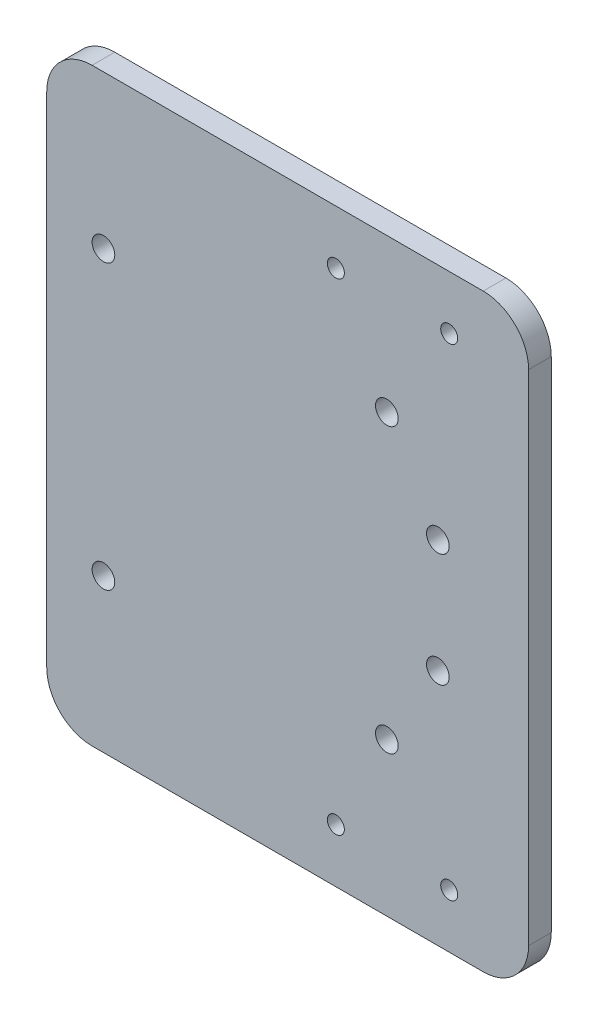
SolidWorks part; units mm, degrees
ref_plane "前视基准面" through (0, 0, 0) normal (0, 0, 1) x (1, 0, 0)
ref_plane "上视基准面" through (0, 0, 0) normal (0, 1, 0) x (1, 0, 0)
ref_plane "右视基准面" through (0, 0, 0) normal (1, 0, 0) x (0, 0, -1)
sketch "草图1" plane through (0, 0, 0) normal (0, 0, 1) x (1, 0, 0)
  line L1 (-56.1003, 41.4797) -> (28.8997, 41.4797)
  line L2 (-56.1003, 41.4797) -> (-56.1003, -62.5203)
  line L3 (-56.1003, -62.5203) -> (28.8997, -62.5203)
  line L4 (28.8997, 41.4797) -> (28.8997, -62.5203)
  line L5 (-46.1003, 14.4797) -> (3.8997, 14.4797)
  line L6 (-46.1003, 14.4797) -> (-46.1003, -35.5203)
  line L7 (-46.1003, -35.5203) -> (3.8997, -35.5203)
  line L8 (3.8997, 14.4797) -> (3.8997, -35.5203)
  line L9 (-5.1003, 31.9797) -> (14.8997, 31.9797)
  line L10 (-5.1003, 31.9797) -> (-5.1003, -53.0203)
  line L11 (-5.1003, -53.0203) -> (14.8997, -53.0203)
  line L12 (14.8997, 31.9797) -> (14.8997, -53.0203)
  circle A0 centre (12.8997, -0.5203) radius 2
  circle A1 centre (12.8997, -20.5203) radius 2
  circle A2 centre (-46.1003, 14.4797) radius 2
  circle A3 centre (-46.1003, -35.5203) radius 2
  circle A4 centre (3.8997, -35.5203) radius 2
  circle A5 centre (3.8997, 14.4797) radius 2
  circle A6 centre (-5.1003, 31.9797) radius 1.5
  circle A7 centre (14.8997, 31.9797) radius 1.5
  circle A8 centre (-5.1003, -53.0203) radius 1.5
  circle A9 centre (14.8997, -53.0203) radius 1.5
  point P8 (-46.1003, -10.5203)
  point P9 (-56.1003, -10.5203)
  point P22 (14.8997, -10.5203)
  point P23 (28.8997, -10.5203)
  dimension "D9" = 85
  dimension "D1" = 104
  dimension "D2" = 85
  dimension "D3" = 50
  dimension "D4" = 50
  dimension "D5" = 10
  dimension "D6" = 16
  dimension "D7" = 20
  dimension "D8" = 42
  dimension "D10" = 14
  dimension "D11" = 20
extrude "凸台-拉伸1" add sketch "草图1" along normal blind 4 contours L4 L1 L2 L3 A9 L11 A8 L10 L7 A3 L6 A2 L5 A6 L9 A7 L12 | A3 L7 L10 L5 A2 L6 | A9 L12 A1 A0 A7 L9 A6 L10 L5 A5 L8 A4 L7 A8 L11 | A5 L5 L10 L7 A4 L8
fillet "圆角1" radius 8 4 edges at (-56.1003, -62.5203, 2) (28.8997, -62.5203, 2) (28.8997, 41.4797, 2) (-56.1003, 41.4797, 2)
